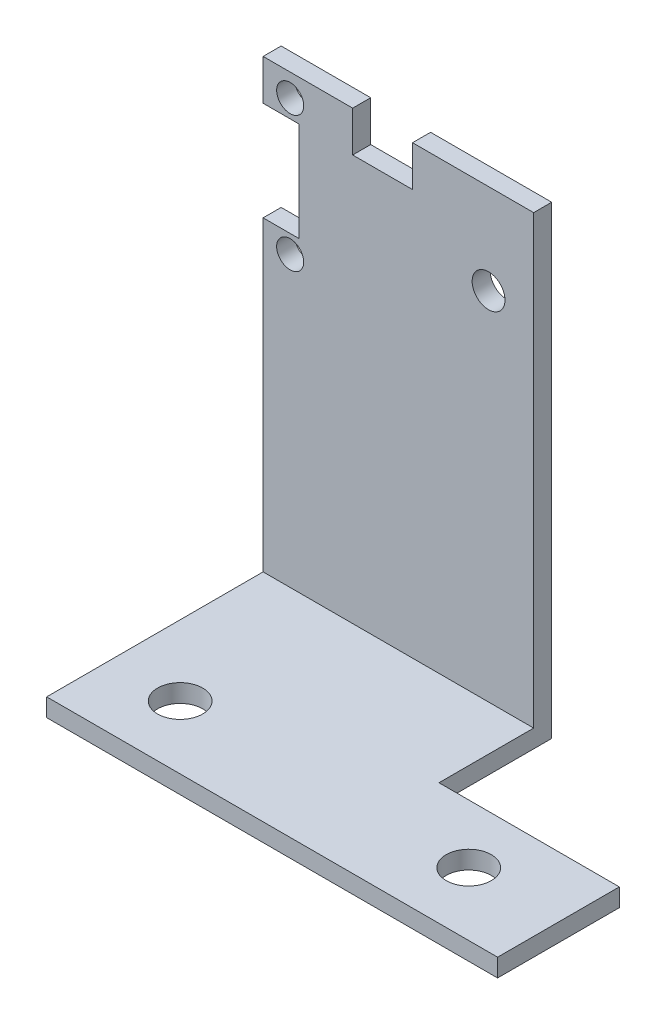
SolidWorks part; units mm, degrees
ref_plane "Ebene vorne" through (0, 0, 0) normal (0, 0, 1) x (1, 0, 0)
ref_plane "Ebene oben" through (0, 0, 0) normal (0, 1, 0) x (1, 0, 0)
ref_plane "Ebene rechts" through (0, 0, 0) normal (1, 0, 0) x (0, 0, -1)
sketch "Skizze1" plane through (0, 0, 0) normal (0, 1, 0) x (1, 0, 0)
  line L1 (-25, -13) -> (25, -13)
  line L2 (-25, -13) -> (-25, 13)
  line L3 (-25, 13) -> (25, 13)
  line L4 (25, -13) -> (25, 13)
  line L5 (-25, -13) -> (25, 13) construction
  line L6 (-25, 13) -> (25, -13) construction
  circle A0 centre (14.8024, -6) radius 2.5
  circle A1 centre (-17.1976, -6) radius 2.5
  point P0 (0, 0)
  dimension "D2" = 5
  dimension "D3" = 5
  dimension "D1" = 32
  dimension "D4" = 50
  dimension "D5" = 7
  dimension "D6" = 19
extrude "Aufsatz-Linear austragen1" add sketch "Skizze1" along normal blind 2
sketch "Skizze2" plane through (0, 2, 0) normal (0, 1, 0) x (1, 0, 0)
  line L1 (-25, 13) -> (5, 13)
  line L2 (-25, 13) -> (-25, 11)
  line L3 (-25, 11) -> (5, 11)
  line L4 (5, 13) -> (5, 11)
  dimension "D1" = 2
  dimension "D2" = 5
extrude "Aufsatz-Linear austragen2" add sketch "Skizze2" along normal blind 49.5
sketch "Skizze3" plane through (0, 0, -11) normal (0, 0, 1) x (1, 0, 0)
  line L0 (-25, 51.5) -> (5, 51.5) construction
  line L1 (-25, 51.5) -> (-25, 2) construction
  line L2 (-25, 47) -> (-21, 47)
  line L3 (-25, 47) -> (-25, 36)
  line L4 (-25, 36) -> (-21, 36)
  line L5 (-21, 47) -> (-21, 36)
  line L7 (-15.0686, 51.5) -> (-8.4293, 51.5)
  line L8 (-15.0686, 51.5) -> (-15.0686, 47)
  line L9 (-15.0686, 47) -> (-8.4293, 47)
  line L10 (-8.4293, 51.5) -> (-8.4293, 47)
  circle A0 centre (-22, 49) radius 1.5
  circle A1 centre (-22, 34) radius 1.5
  circle A2 centre (0, 41.5) radius 1.8226
  dimension "D3" = 3
  dimension "D4" = 3
  dimension "D1" = 0
  dimension "D2" = 10
  dimension "D5" = 15
  dimension "D6" = 2.5
  dimension "D7" = 22
  dimension "D8" = 2
  dimension "D9" = 2
  dimension "D10" = 4
extrude "Schnitt-Linear austragen1" cut sketch "Skizze3" against normal blind 49.5
sketch "Skizze4" plane through (0, 2, 0) normal (0, 1, 0) x (1, 0, 0)
  line L1 (25, 13) -> (5, 13)
  line L2 (25, 13) -> (25, 0.5)
  line L3 (25, 0.5) -> (5, 0.5)
  line L4 (5, 13) -> (5, 0.5)
  dimension "D1" = 20
  dimension "D2" = 12.5
extrude "Schnitt-Linear austragen2" cut sketch "Skizze4" against normal blind 49.5
